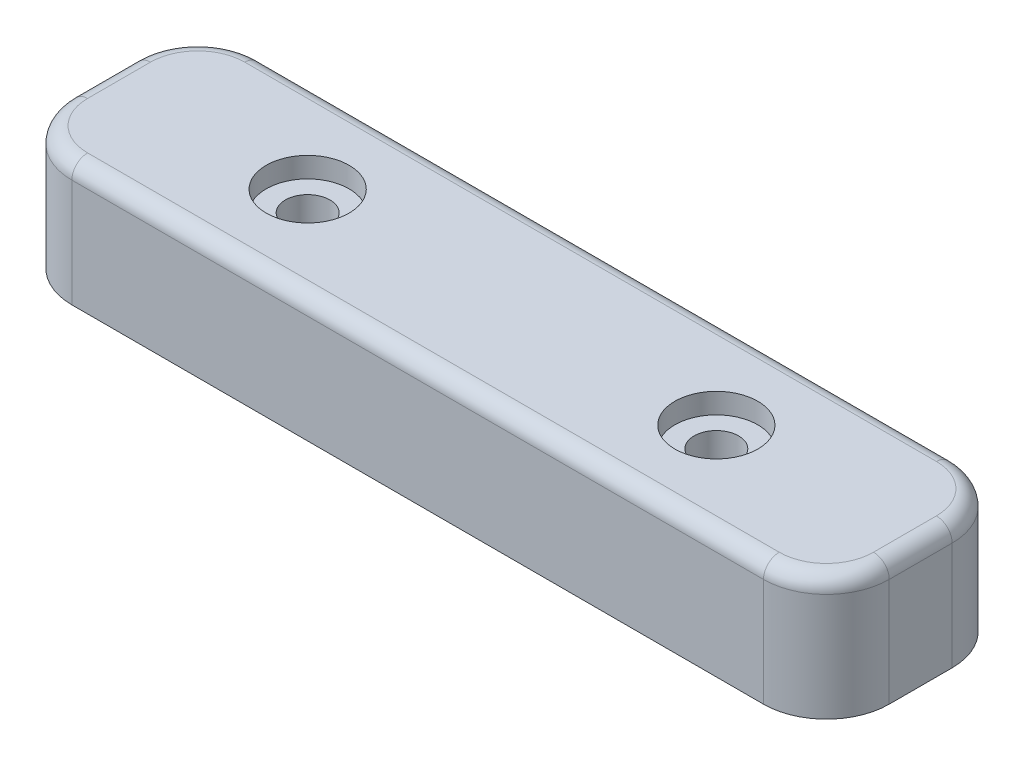
SolidWorks part; units mm, degrees
material "ABS"
ref_plane "Front Plane" through (0, 0, 0) normal (0, 0, 1) x (1, 0, 0)
ref_plane "Top Plane" through (0, 0, 0) normal (0, 1, 0) x (1, 0, 0)
ref_plane "Right Plane" through (0, 0, 0) normal (1, 0, 0) x (0, 0, -1)
sketch "Sketch1" plane through (0, 0, 0) normal (0, 1, 0) x (1, 0, 0)
  line L1 (0, 0) -> (66.04, 0)
  line L2 (0, 0) -> (0, -15.24)
  line L3 (0, -15.24) -> (66.04, -15.24)
  line L4 (66.04, 0) -> (66.04, -15.24)
  dimension "D1" = 66.04
  dimension "D2" = 15.24
extrude "Boss-Extrude1" add sketch "Sketch1" along normal blind 10
sketch "Sketch2" plane through (0, 10, 0) normal (0, 1, 0) x (1, 0, 0)
  line L0 (0, -7.62) -> (66.04, -7.62) construction
  line L1 (0, 0) -> (0, -15.24) construction
  line L2 (66.04, -15.24) -> (66.04, 0) construction
  line L3 (16.51, 0) -> (16.51, -15.24) construction
  line L4 (66.04, 0) -> (0, 0) construction
  line L5 (0, -15.24) -> (66.04, -15.24) construction
  line L6 (49.53, 0) -> (49.53, -15.24) construction
  circle A0 centre (16.51, -7.62) radius 1.6 construction
  circle A1 centre (49.53, -7.62) radius 1.6 construction
  dimension "D3" = 3.2
  dimension "D1" = 16.51
  dimension "D2" = 16.51
hole_wizard "CBORE for M3 SBHCS1" positions "Sketch3" profile "Sketch4" counterbore size "M3" standard "ANSI Metric" end condition through all
sketch "Sketch3" plane through (0, 10, 0) normal (0, 1, 0) x (1, 0, 0)
  point P0 (16.51, -7.62)
  point P3 (49.53, -7.62)
sketch "Sketch4" plane through (16.51, 10, 7.62) normal (1, 0, 0) x (0, 0, 1)
  line L0 (0, 0) -> (0, 10)
  line L1 (0, 10) -> (1.8, 10)
  line L3 (1.8, 10) -> (1.8, 1.65)
  line L4 (1.8, 1.65) -> (3.35, 1.65)
  line L5 (3.35, 1.65) -> (3.35, 0)
  line L7 (3.35, 0) -> (0, 0)
  line L11 (0, -6.35) -> (0, 107.95) construction
  dimension "Thru Hole Dia." = 3.6
  dimension "Thru Hole Depth" = 10
  dimension "C'Bore Dia." = 6.7
  dimension "C'Bore Depth" = 1.65
fillet "Fillet1" radius 5.08 4 edges at (0, 5, 15.24) (0, 5, 0) (66.04, 5, 15.24) (66.04, 5, 0)
fillet "Fillet2" radius 1.27 8 edges at (1.4879, 10, 13.7521) (0, 10, 7.62) (1.4879, 10, 1.4879) (33.02, 10, 0) (64.5521, 10, 1.4879) (66.04, 10, 7.62) (64.5521, 10, 13.7521) (33.02, 10, 15.24)
